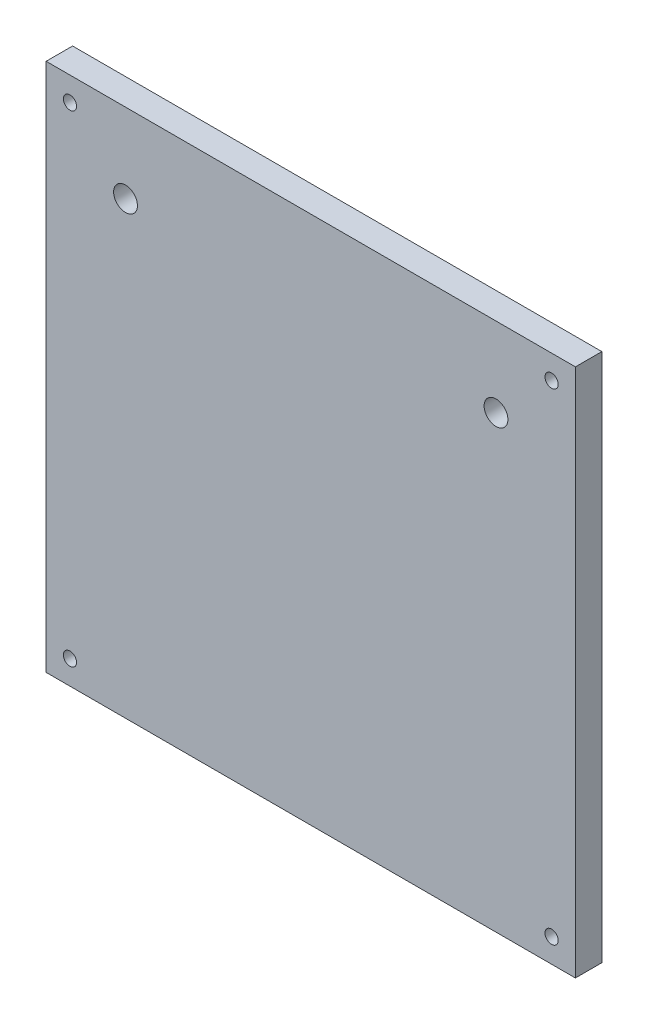
SolidWorks part; units mm, degrees
ref_plane "Front Plane" through (0, 0, 0) normal (0, 0, 1) x (1, 0, 0)
ref_plane "Top Plane" through (0, 0, 0) normal (0, 1, 0) x (1, 0, 0)
ref_plane "Right Plane" through (0, 0, 0) normal (1, 0, 0) x (0, 0, -1)
sketch "Sketch1" plane through (0, 0, 0) normal (0, 0, 1) x (1, 0, 0)
  line L0 (-50, 35) -> (50, 35) construction
  line L1 (50, -50) -> (-50, -50)
  line L2 (50, -50) -> (50, 50)
  line L3 (50, 50) -> (-50, 50)
  line L4 (-50, -50) -> (-50, 50)
  line L5 (50, -50) -> (-50, 50) construction
  line L6 (50, 50) -> (-50, -50) construction
  line L7 (45.5, 45.5) -> (-45.5, 45.5) construction
  line L8 (45.5, 45.5) -> (45.5, -45.5) construction
  line L9 (45.5, -45.5) -> (-45.5, -45.5) construction
  line L10 (-45.5, 45.5) -> (-45.5, -45.5) construction
  line L11 (45.5, 45.5) -> (-45.5, -45.5) construction
  line L12 (45.5, -45.5) -> (-45.5, 45.5) construction
  circle A0 centre (-45.5, 45.5) radius 1.25
  circle A1 centre (45.5, 45.5) radius 1.25
  circle A2 centre (45.5, -45.5) radius 1.25
  circle A3 centre (-45.5, -45.5) radius 1.25
  circle A4 centre (-35, 35) radius 2.25
  circle A5 centre (35, 35) radius 2.25
  point P0 (0, 0)
  point P5 (0, 0)
  dimension "D5" = 2.5
  dimension "D6" = 2.5
  dimension "D7" = 2.5
  dimension "D8" = 2.5
  dimension "D9" = 15
  dimension "D10" = 15
  dimension "D11" = 4.5
  dimension "D12" = 4.5
  dimension "D1" = 100
  dimension "D2" = 100
  dimension "D3" = 91
  dimension "D4" = 15
extrude "Boss-Extrude1" add sketch "Sketch1" along normal blind 5
